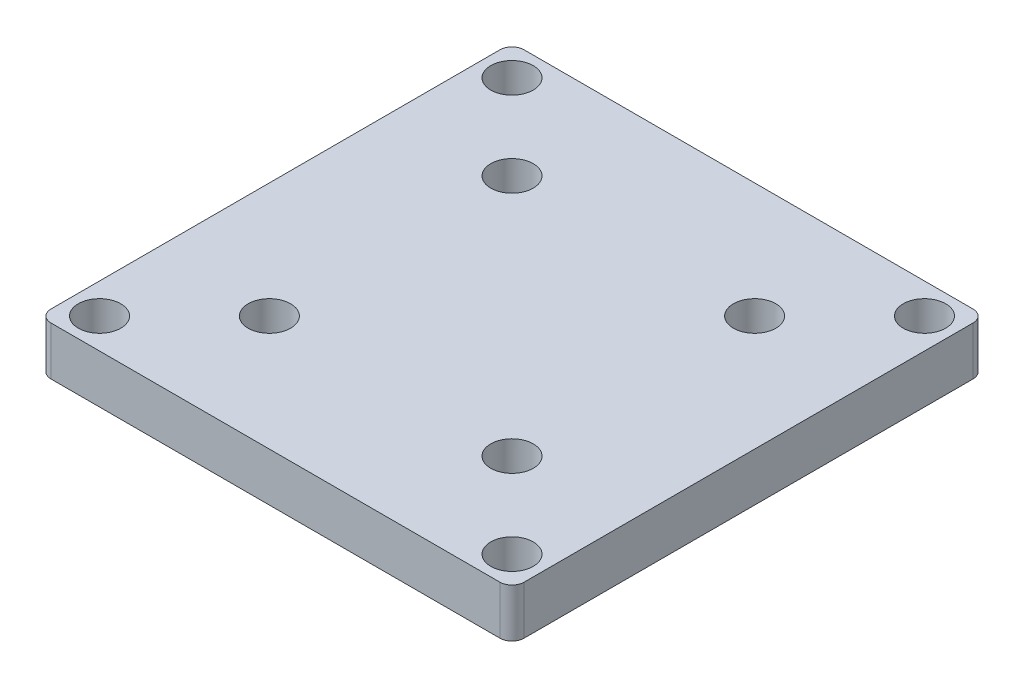
SolidWorks part; units mm, degrees
ref_plane "Front Plane" through (0, 0, 0) normal (0, 0, 1) x (1, 0, 0)
ref_plane "Top Plane" through (0, 0, 0) normal (0, 1, 0) x (1, 0, 0)
ref_plane "Right Plane" through (0, 0, 0) normal (1, 0, 0) x (0, 0, -1)
sketch "Sketch1" plane through (0, 0, 0) normal (0, 1, 0) x (1, 0, 0)
  line L5 (-17, -17) -> (17, -17) construction
  line L6 (-17, -17) -> (-17, 17) construction
  line L7 (-17, 17) -> (17, 17) construction
  line L8 (17, -17) -> (17, 17) construction
  line L9 (-17, -17) -> (17, 17) construction
  line L10 (-17, 17) -> (17, -17) construction
  line L11 (-19.5, -19.5) -> (19.5, -19.5)
  line L12 (-19.5, -19.5) -> (-19.5, 19.5)
  line L13 (-19.5, 19.5) -> (19.5, 19.5)
  line L14 (19.5, -19.5) -> (19.5, 19.5)
  line L15 (-19.5, -19.5) -> (19.5, 19.5) construction
  line L16 (-19.5, 19.5) -> (19.5, -19.5) construction
  circle A0 centre (17, 17) radius 1.75
  circle A1 centre (17, -17) radius 1.75
  circle A2 centre (-17, -17) radius 1.75
  circle A3 centre (-17, 17) radius 1.75
  point P0 (0, 0)
  point P1 (0, 0)
  point P6 (0, 0)
  point P21 (0, 0)
  dimension "D5" = 3.5
  dimension "D1" = 39
  dimension "D2" = 39
  dimension "D3" = 34
  dimension "D4" = 34
  dimension "D6" = 4
extrude "Boss-Extrude1" add sketch "Sketch1" along normal blind 4
sketch "Sketch2" plane through (0, 4, 0) normal (0, 1, 0) x (1, 0, 0)
  line L1 (-10, -10) -> (10, -10) construction
  line L2 (-10, -10) -> (-10, 10) construction
  line L3 (-10, 10) -> (10, 10) construction
  line L4 (10, -10) -> (10, 10) construction
  line L5 (-10, -10) -> (10, 10) construction
  line L6 (-10, 10) -> (10, -10) construction
  circle A0 centre (10, 10) radius 1.75
  circle A1 centre (10, -10) radius 1.75
  circle A2 centre (-10, -10) radius 1.75
  circle A3 centre (-10, 10) radius 1.75
  point P0 (0, 0)
  point P16 (0, 0)
  dimension "D1" = 3.5
  dimension "D2" = 20
  dimension "D3" = 20
  dimension "D4" = 4
extrude "Cut-Extrude1" cut sketch "Sketch2" against normal blind 11
fillet "Fillet1" radius 1 4 edges at (-19.5, 2, 19.5) (-19.5, 2, -19.5) (19.5, 2, -19.5) (19.5, 2, 19.5)
